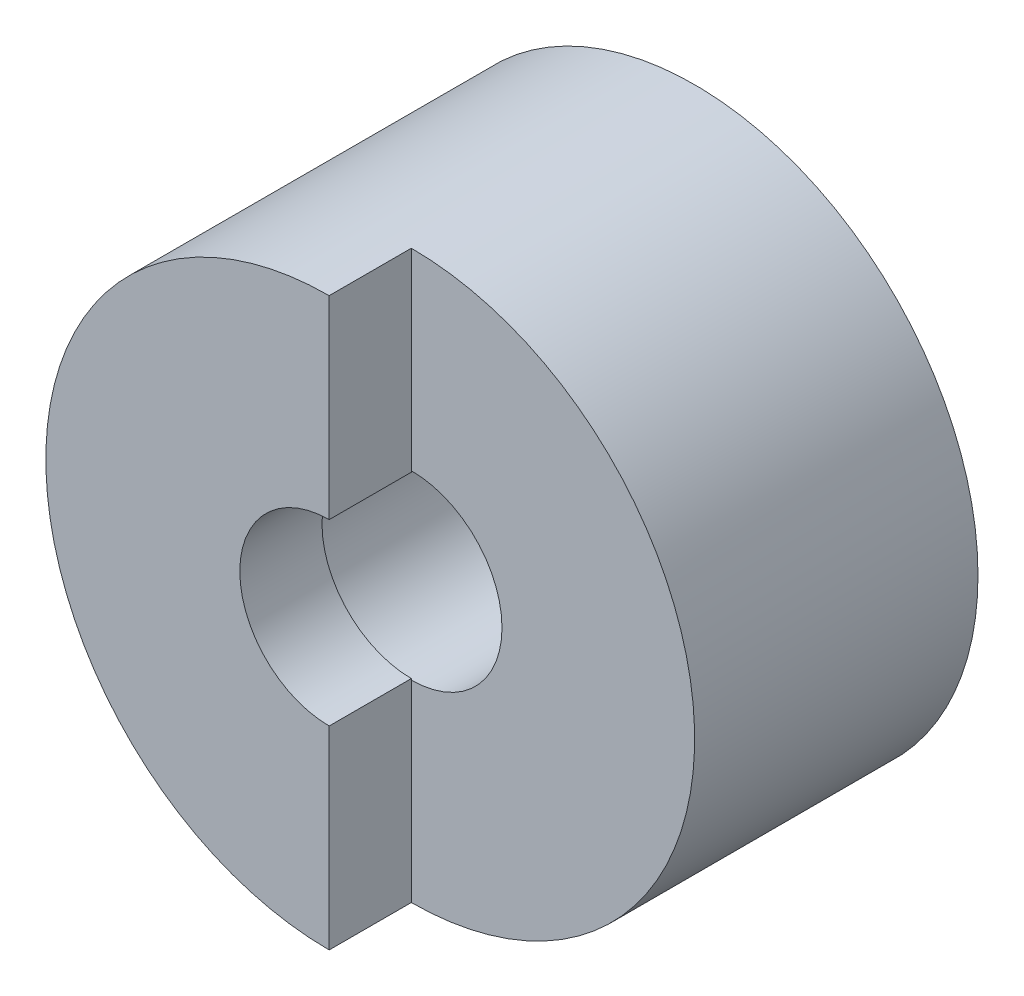
SolidWorks part; units mm, degrees
ref_plane "Front Plane" through (0, 0, 0) normal (0, 0, 1) x (1, 0, 0)
ref_plane "Top Plane" through (0, 0, 0) normal (0, 1, 0) x (1, 0, 0)
ref_plane "Right Plane" through (0, 0, 0) normal (1, 0, 0) x (0, 0, -1)
sketch "Sketch2" plane through (0, 0, 0) normal (0, 0, 1) x (1, 0, 0)
  circle A0 centre (0, 0) radius 5
  circle A1 centre (0, 0) radius 1.6
  dimension "D1" = 10
  dimension "D2" = 3.2
extrude "Boss-Extrude1" add sketch "Sketch2" along normal blind 5
sketch "Sketch3" plane through (0, 0, 5) normal (0, 0, 1) x (1, 0, 0)
  line L0 (0, 1.5767) -> (0, 5)
  line L1 (0, -1.5767) -> (0, -5)
  arc A0 (0, 5) -> (0, -5) centre (0, 0) ccw
  arc A1 (0, 1.5767) -> (0, -1.5767) centre (0, 0) ccw
extrude "Boss-Extrude2" add sketch "Sketch3" along normal blind 1.45
